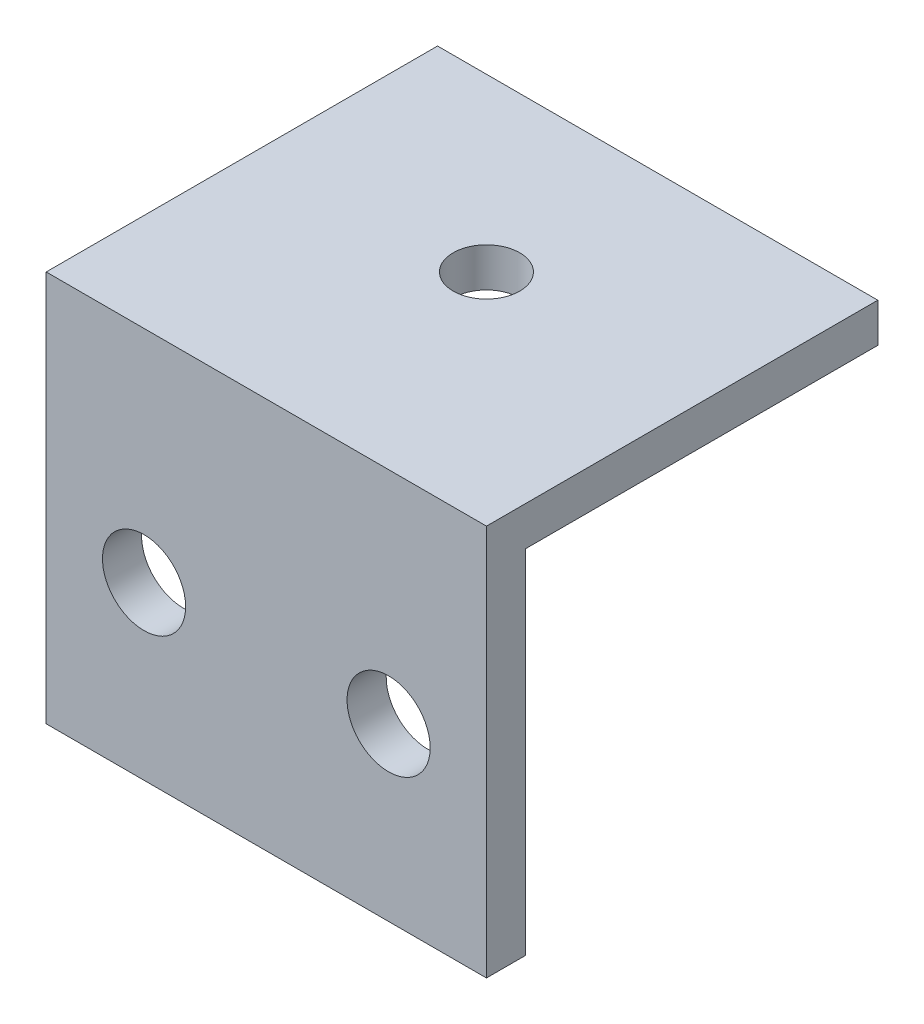
SolidWorks part; units mm, degrees
ref_plane "Front" through (0, 0, 0) normal (0, 0, 1) x (1, 0, 0)
ref_plane "Top" through (0, 0, 0) normal (0, 1, 0) x (1, 0, 0)
ref_plane "Right" through (0, 0, 0) normal (1, 0, 0) x (0, 0, -1)
sketch "Sketch1" plane through (0, 0, 0) normal (1, 0, 0) x (0, 0, -1)
  line L0 (0, -40) -> (0, 0)
  line L1 (0, 0) -> (40, 0)
  line L2 (40, 0) -> (40, -4)
  line L3 (40, -4) -> (4, -4)
  line L4 (4, -4) -> (4, -40)
  line L5 (4, -40) -> (0, -40)
  dimension "D1" = 40
  dimension "D2" = 4
extrude "Boss-Extrude1" add sketch "Sketch1" along normal mid plane 45
hole_wizard "Ø8.5 (8.5) Diameter Hole1" positions "Sketch2" profile "Sketch3" hole size "Ø8.5" standard "ISO"
sketch "Sketch2" plane through (0, 0, 0) normal (0, 0, 1) x (1, 0, 0)
  line L0 (22.5, -40) -> (-22.5, -40) construction
  point P0 (0, -32.5)
  point P2 (0, -15)
  point P5 (0, 0)
  dimension "D1" = 17.5
  dimension "D2" = 7.5
sketch "Sketch3" plane through (0, -32.5, 0) normal (1, 0, 0) x (0, -1, 0)
  line L0 (0, 0) -> (0, 40)
  line L1 (0, 40) -> (4.25, 40)
  line L2 (4.25, 40) -> (4.25, 0)
  line L5 (4.25, 0) -> (0, 0)
  line L11 (0, -6.35) -> (0, 107.95) construction
  dimension "Thru Hole Dia." = 8.5
  dimension "Thru Hole Depth" = 40
hole_wizard "M8 Tapped Hole1" positions "Sketch4" profile "Sketch5" tap size "M8" standard "ISO" end condition through all
sketch "Sketch4" plane through (0, 0, 0) normal (0, 1, 0) x (1, 0, 0)
  line L0 (22.5, 0) -> (-22.5, 0) construction
  point P0 (0, 22.5)
  point P5 (0, 0)
  dimension "D1" = 22.5
sketch "Sketch5" plane through (0, 0, -22.5) normal (1, 0, 0) x (0, 0, 1)
  line L0 (0, 0) -> (0, 40)
  line L1 (0, 40) -> (3.4, 40)
  line L2 (3.4, 40) -> (3.4, 0)
  line L5 (3.4, 0) -> (0, 0)
  line L11 (0, -6.35) -> (0, 107.95) construction
  dimension "Thru Tap Drill Dia." = 6.8
  dimension "Thru Tap Drill Depth" = 40
cosmetic thread "Hole Thread1" parameters "D2"=8
hole_wizard "Ø8.5 (8.5) Diameter Hole2" positions "Sketch6" profile "Sketch7" hole size "Ø8.5" standard "ISO" end condition through all
sketch "Sketch6" plane through (0, 0, 0) normal (0, 0, 1) x (1, 0, 0)
  line L0 (22.5, 0) -> (-22.5, 0) construction
  point P0 (-12.5, -22.5)
  point P2 (12.5, -22.5)
  dimension "D1" = 25
  dimension "D2" = 22.5
  dimension "D3" = 12.5
sketch "Sketch7" plane through (-12.5, -22.5, 0) normal (1, 0, 0) x (0, -1, 0)
  line L0 (0, 0) -> (0, 40)
  line L1 (0, 40) -> (4.25, 40)
  line L2 (4.25, 40) -> (4.25, 0)
  line L5 (4.25, 0) -> (0, 0)
  line L11 (0, -6.35) -> (0, 107.95) construction
  dimension "Thru Hole Dia." = 8.5
  dimension "Thru Hole Depth" = 40
